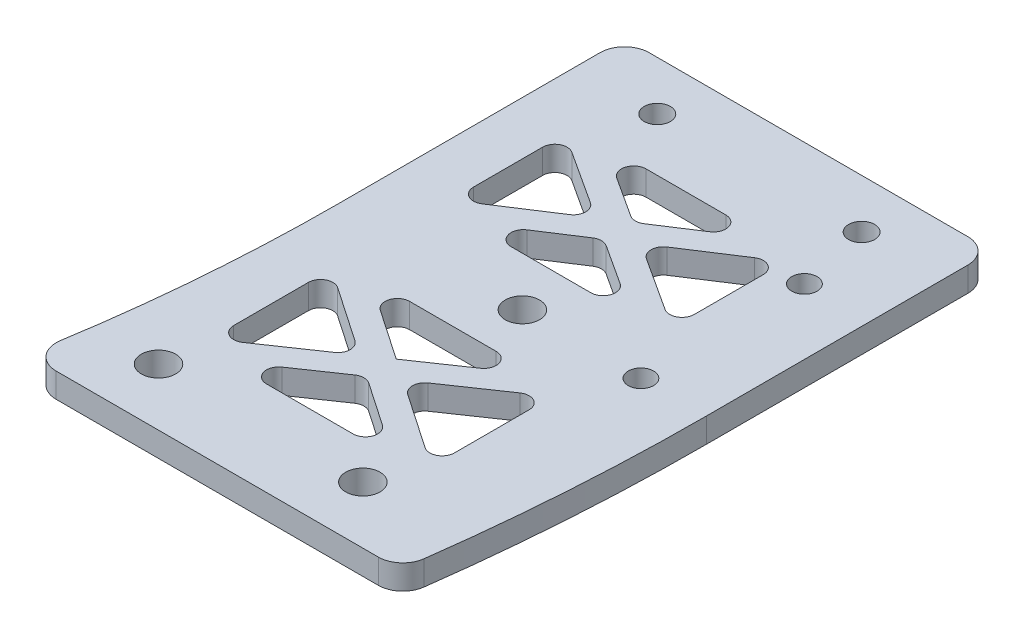
SolidWorks part; units mm, degrees
material "Thornel Mat VMA"
ref_plane "前视基准面" through (0, 0, 0) normal (0, 0, 1) x (1, 0, 0)
ref_plane "上视基准面" through (0, 0, 0) normal (0, 1, 0) x (1, 0, 0)
ref_plane "右视基准面" through (0, 0, 0) normal (1, 0, 0) x (0, 0, -1)
other "Configuration Table"
sketch "草图1" plane through (0, 0, 0) normal (0, 1, 0) x (1, 0, 0)
  line L0 (-22.5, 0) -> (-22.5, 35)
  line L5 (-22.5, 35) -> (22.5, 35)
  line L6 (22.5, 35) -> (22.5, 0)
  line L7 (-25.5863, -35) -> (19.9871, -35)
  arc A2 (-25.5863, -35) -> (-22.5, 0) centre (-222.5, 0) ccw
  arc A3 (19.9871, -35) -> (22.5, 0) centre (-222.5, 0) ccw
  circle A4 centre (0, 0) radius 2.1
  point P14 (0, 35)
  dimension "D5" = 4.2
  dimension "D2" = 400
  dimension "D1" = 45
  dimension "D3" = 70
  dimension "D4" = 35
extrude "凸台-拉伸1" add sketch "草图1" along normal blind 3
sketch "草图2" plane through (0, 3, 0) normal (0, 1, 0) x (1, 0, 0)
  line L0 (-16.5129, -28) -> (8.4871, -28) construction
  line L1 (-4.0129, -28) -> (-4.0129, -35) construction
  line L3 (-25.5863, -35) -> (19.9871, -35) construction
  line L4 (-12.5, 29) -> (12.5, 29) construction
  line L5 (0, 0) -> (0, 29) construction
  line L6 (22.5, 35) -> (-22.5, 35) construction
  circle A0 centre (-16.5129, -28) radius 2.1
  circle A1 centre (8.4871, -28) radius 2.1
  circle A2 centre (-12.5, 29) radius 1.6
  circle A3 centre (12.5, 29) radius 1.6
  dimension "D3" = 4.2
  dimension "D7" = 3.2
  dimension "D1" = 7
  dimension "D2" = 25
  dimension "D4" = 24
  dimension "D5" = 6
  dimension "D6" = 25
extrude "切除-拉伸1" cut sketch "草图2" against normal blind 3
fillet "圆角1" radius 3 4 edges at (-22.5, 1.5, -35) (22.5, 1.5, -35) (19.9871, 1.5, 35) (-25.5863, 1.5, 35)
sketch "草图3" plane through (0, 3, 0) normal (0, 1, 0) x (1, 0, 0)
  line L0 (-18.5784, -21) -> (16.5795, -21)
  line L1 (17.425, -6) -> (-17.5878, -6)
  arc A0 (-18.5784, -21) -> (-17.5878, -6) centre (-222.5, 0) ccw
  arc A1 (16.5795, -21) -> (17.425, -6) centre (-222.5, 0) ccw
  circle A2 centre (0, 0) radius 2.1 construction
  arc A3 (20.3486, -32.3967) -> (22.5, 0) centre (-222.5, 0) ccw construction
  arc A5 (-25.0005, -31.5271) -> (-22.5, 0) centre (-222.5, 0) ccw construction
  circle A6 centre (8.4871, -28) radius 2.1 construction
  dimension "D2" = 5
  dimension "D3" = 5
  dimension "D1" = 6
  dimension "D4" = 7
extrude "切除-拉伸2" [suppressed] cut sketch "草图3" against normal blind 10
sketch "草图5" plane through (0, 0, 0) normal (0, -1, 0) x (1, 0, 0)
  line L0 (22.5, 0) -> (14.5, 0) construction
  line L1 (14.5, 0) -> (14.5, -20) construction
  line L2 (14.5, -20) -> (22.5, -20) construction
  line L3 (22.5, 0) -> (22.5, -32) construction
  circle A0 centre (14.5, 0) radius 1.55
  circle A1 centre (14.5, -20) radius 1.55
  circle A2 centre (12.5, -29) radius 1.6 construction
  dimension "D4" = 3.1
  dimension "D1" = 20
  dimension "D2" = 8
  dimension "D3" = 9
extrude "切除-拉伸3" cut sketch "草图5" against normal blind 10
fillet "圆角4" [suppressed] radius 2
sketch "草图6" plane through (0, 3, 0) normal (0, 1, 0) x (1, 0, 0)
  line L0 (-17.5, -4.5) -> (-17.5, -25)
  line L1 (-17.5, -25) -> (12.5, -25)
  line L2 (12.5, -25) -> (12.5, -4.5)
  line L3 (12.5, -4.5) -> (-17.5, -4.5)
  line L4 (-17.5, 24) -> (12.5, 24)
  line L5 (12.5, 24) -> (12.5, 4.5)
  line L6 (12.5, 4.5) -> (-17.5, 4.5)
  line L7 (-17.5, 4.5) -> (-17.5, 24)
  line L8 (-22.5, 32) -> (-22.5, 0) construction
  line L9 (-17.5, 24) -> (12.5, 4.5)
  line L10 (12.5, 24) -> (-17.5, 4.5)
  line L11 (-17.5, -4.5) -> (12.5, -25)
  line L12 (12.5, -4.5) -> (-17.5, -25)
  line L13 (-19, -4.5) -> (-19, -25)
  line L14 (-17.5, -26.5) -> (12.5, -26.5)
  line L15 (14, -25) -> (14, -4.5)
  line L16 (12.5, -3) -> (-17.5, -3)
  line L17 (-17.5, 22.5) -> (12.5, 22.5)
  line L18 (11, 24) -> (11, 4.5)
  line L19 (12.5, 6) -> (-17.5, 6)
  line L20 (-16, 4.5) -> (-16, 24)
  line L21 (-18.3175, 22.7423) -> (11.6825, 3.2423)
  line L22 (11.6825, 25.2577) -> (-18.3175, 5.7577)
  line L23 (-18.3463, -5.7385) -> (11.6537, -26.2385)
  line L24 (11.6537, -3.2615) -> (-18.3463, -23.7615)
  line L25 (-16, -4.5) -> (-16, -25)
  line L26 (-17.5, -23.5) -> (12.5, -23.5)
  line L27 (11, -25) -> (11, -4.5)
  line L28 (12.5, -6) -> (-17.5, -6)
  line L29 (-17.5, 25.5) -> (12.5, 25.5)
  line L30 (14, 24) -> (14, 4.5)
  line L31 (12.5, 3) -> (-17.5, 3)
  line L32 (-19, 4.5) -> (-19, 24)
  line L33 (-16.6825, 25.2577) -> (13.3175, 5.7577)
  line L34 (13.3175, 22.7423) -> (-16.6825, 3.2423)
  line L35 (-16.6537, -3.2615) -> (13.3463, -23.7615)
  line L36 (13.3463, -5.7385) -> (-16.6537, -26.2385)
  circle A0 centre (-16.5129, -28) radius 2.1 construction
  circle A1 centre (12.5, 29) radius 1.6 construction
  circle A2 centre (-12.5, 29) radius 1.6 construction
  dimension "D6" = 5
  dimension "D1" = 4.5
  dimension "D2" = 4.5
  dimension "D3" = 3
  dimension "D4" = 5
  dimension "D5" = 0
  dimension "D7" = 1.5
  dimension "D8" = 1.5
extrude "切除-拉伸4" cut sketch "草图6" against normal blind 3 contours L17 L33 L22 | L22 L21 L20 | L21 L34 L19 | L18 L34 L33 | L28 L35 L24 | L23 L25 L24 | L23 L36 L26 | L27 L36 L35
fillet "圆角5" radius 1.5 23 edges at (7.6462, 1.5, 23.5) (-2.5, 1.5, 16.5668) (11, 1.5, 22.1582) (0.1587, 1.5, 14.75) (11, 1.5, 7.3418) (7.6462, 1.5, 6) (-5.1587, 1.5, 14.75) (-16, 1.5, 22.1582) (-16, 1.5, 7.3418) (-12.6462, 1.5, 23.5) (-12.6462, 1.5, 6) (0.2524, 1.5, -14.25) (11, 1.5, -21.236) (11, 1.5, -7.264) (-2.5, 1.5, -12.461) (7.44, 1.5, -6) (-12.44, 1.5, -6) (7.44, 1.5, -22.5) (-2.5, 1.5, -16.039) (-5.2524, 1.5, -14.25) (-16, 1.5, -7.264) (-16, 1.5, -21.236) (-12.44, 1.5, -22.5)
